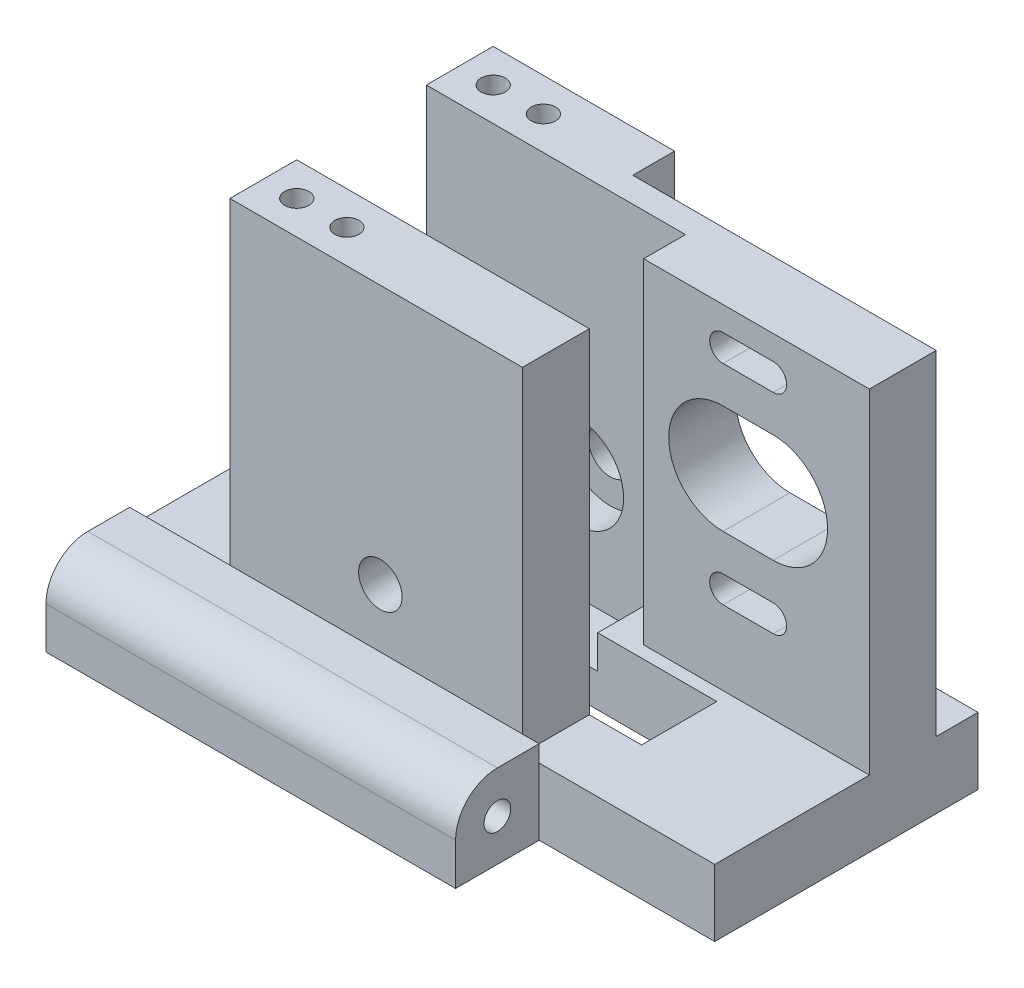
SolidWorks part; units mm, degrees
ref_plane "Front" through (0, 0, 0) normal (0, 0, 1) x (1, 0, 0)
ref_plane "Top" through (0, 0, 0) normal (0, 1, 0) x (1, 0, 0)
ref_plane "Right" through (0, 0, 0) normal (1, 0, 0) x (0, 0, -1)
sketch "Sketch1" plane through (0, 0, 0) normal (0, 1, 0) x (1, 0, 0)
  line L1 (0, 0) -> (70, 0)
  line L2 (0, 0) -> (0, -31.5)
  line L3 (0, -31.5) -> (70, -31.5)
  line L4 (70, 0) -> (70, -31.5)
  dimension "D1" = 70
  dimension "D2" = 31.5
extrude "Boss-Extrude1" add sketch "Sketch1" along normal blind 8
sketch "Sketch2" plane through (0, 8, 0) normal (0, 1, 0) x (1, 0, 0)
  line L1 (12, -31.5) -> (47, -31.5)
  line L2 (0, 0) -> (0, -31.5) construction
  line L3 (12, -23.5) -> (47, -23.5)
  line L6 (47, 0) -> (12, 0)
  line L8 (47, -8) -> (12, -8)
  line L10 (12, -8) -> (12, 0)
  line L11 (47, -8) -> (47, 0)
  line L12 (12, -23.5) -> (12, -31.5)
  line L13 (47, -23.5) -> (47, -31.5)
  dimension "D1" = 8
  dimension "D2" = 8
  dimension "D3" = 35
  dimension "D4" = 12
extrude "Boss-Extrude2" add sketch "Sketch2" along normal blind 20
sketch "Sketch3" plane through (0, 0, 31.5) normal (0, 0, 1) x (1, 0, 0)
  line L0 (0, 8) -> (0, 0) construction
  line L1 (0, 0) -> (70, 0) construction
  circle A0 centre (30, 17) radius 2.6
  dimension "D1" = 5.2
  dimension "D2" = 30
  dimension "D3" = 17
extrude "Cut-Extrude1" cut sketch "Sketch3" against normal through all
sketch "Sketch4" plane through (0, 0, 0) normal (0, 0, -1) x (-1, 0, 0)
  line L0 (-70, 0) -> (0, 0) construction
  line L1 (-49, 0) -> (0, 0)
  line L2 (-49, 0) -> (-49, 10)
  line L3 (-49, 10) -> (0, 10)
  line L4 (0, 0) -> (0, 10)
  dimension "D1" = 49
  dimension "D2" = 21
  dimension "D3" = 10
extrude "Boss-Extrude3" add sketch "Sketch4" along normal blind 10
sketch "Sketch5" plane through (0, 0, 0) normal (-1, 0, 0) x (0, 0, 1)
  line L0 (-10, 10) -> (0, 10) construction
  line L1 (-10, 0) -> (-10, 10) construction
  circle A0 centre (-5, 5) radius 1.6
  dimension "D1" = 3.2
  dimension "D2" = 5
  dimension "D3" = 5
extrude "Cut-Extrude2" cut sketch "Sketch5" against normal through all
sketch "Sketch6" plane through (0, 8, 0) normal (0, 1, 0) x (1, 0, 0)
  line L0 (47, -23.5) -> (12, -23.5) construction
  line L1 (7.25, -23.5) -> (53.25, -23.5)
  line L2 (7.25, -23.5) -> (7.25, -14.5)
  line L3 (7.25, -14.5) -> (53.25, -14.5)
  line L4 (53.25, -23.5) -> (53.25, -14.5)
  line L6 (0, 0) -> (0, -31.5) construction
  dimension "D1" = 9
  dimension "D2" = 46
  dimension "D3" = 7.25
extrude "Cut-Extrude3" cut sketch "Sketch6" against normal through all
sketch "Sketch7" plane through (0, 0, 8) normal (0, 0, 1) x (1, 0, 0)
  circle A0 centre (30, 17) radius 5.6
  dimension "D1" = 11.2
extrude "Cut-Extrude4" cut sketch "Sketch7" against normal blind 4
sketch "Sketch8" plane through (0, 0, 23.5) normal (0, 0, -1) x (-1, 0, 0)
  circle A0 centre (-30, 17) radius 5.6
  dimension "D1" = 11.2
extrude "Cut-Extrude5" cut sketch "Sketch8" against normal blind 4
sketch "Sketch9" plane through (0, 8, 0) normal (0, 1, 0) x (1, 0, 0)
  line L0 (12, -8) -> (47, -8) construction
  line L1 (21, -8) -> (39, -8)
  line L2 (21, -8) -> (21, -14.5)
  line L3 (21, -14.5) -> (39, -14.5)
  line L4 (39, -8) -> (39, -14.5)
  line L5 (53.25, -14.5) -> (7.25, -14.5) construction
  line L6 (0, 0) -> (0, -31.5) construction
  dimension "D1" = 18
  dimension "D2" = 21
extrude "Cut-Extrude6" cut sketch "Sketch9" against normal blind 4
sketch "Sketch13" plane through (0, 8, 0) normal (0, 1, 0) x (1, 0, 0)
  line L0 (70, -13) -> (43, -13)
  line L1 (70, -31.5) -> (70, 0) construction
  line L2 (43, -13) -> (43, -8)
  line L3 (39, -8) -> (47, -8) construction
  line L4 (43, -8) -> (47, -8)
  line L5 (47, -8) -> (47, -5)
  line L6 (47, -8) -> (47, 0) construction
  line L7 (47, -5) -> (70, -5)
  line L8 (70, -5) -> (70, -13)
  dimension "D1" = 5
  dimension "D2" = 3
  dimension "D3" = 27
extrude "Boss-Extrude5" add sketch "Sketch13" along normal blind 20
sketch "Sketch14" plane through (0, 0, 0) normal (0, 0, -1) x (-1, 0, 0)
  line L0 (-33.6979, 28) -> (-40.8745, 10)
  line L1 (-47, 28) -> (-12, 28) construction
  line L2 (-12, 10) -> (-47, 10) construction
  line L3 (-40.8745, 10) -> (-47, 10)
  line L4 (-47, 28) -> (-47, 10) construction
  line L5 (-47, 10) -> (-49, 10) construction
  line L6 (-47, 10) -> (-47, 28)
  line L7 (-47, 28) -> (-33.6979, 28)
extrude "Cut-Extrude10" cut sketch "Sketch14" against normal blind 5
sketch "Sketch15" plane through (0, 28, 0) normal (0, 1, 0) x (1, 0, 0)
  line L0 (70, -5) -> (70, -13)
  line L1 (70, -13) -> (70, -5) construction
  line L2 (70, -5) -> (33.6979, -5) construction
  line L3 (70, -13) -> (43, -13)
  line L4 (43, -13) -> (70, -13) construction
  line L5 (43, -13) -> (43, -8)
  line L6 (43, -8) -> (43, -13) construction
  line L7 (12, -8) -> (43, -8) construction
  line L8 (70, -5) -> (33.6979, -5)
  line L9 (12, 0) -> (24.1578, 0)
  line L10 (33.6979, -8) -> (43, -8)
  line L11 (33.6979, -8) -> (24.1578, -8)
  line L12 (12, -8) -> (24.1578, -8)
  line L13 (33.6979, 0) -> (12, 0) construction
  line L14 (24.1578, 0) -> (33.6979, 0)
  line L15 (33.6979, 0) -> (33.6979, -5)
  line L16 (12, 0) -> (12, -8)
extrude "Boss-Extrude6" add sketch "Sketch15" along normal blind 20
sketch "Sketch16" plane through (0, 0, 13) normal (0, 0, 1) x (1, 0, 0)
  line L0 (52.5, 31) -> (58.5, 31) construction
  line L1 (52.5, 37.5) -> (58.5, 37.5)
  line L3 (52.5, 24.5) -> (58.5, 24.5)
  line L4 (70, 48) -> (70, 8) construction
  line L5 (43, 48) -> (70, 48) construction
  line L6 (52.5, 43.5) -> (58.5, 43.5) construction
  line L7 (52.5, 45.1) -> (58.5, 45.1)
  line L8 (52.5, 41.9) -> (58.5, 41.9)
  line L9 (52.5, 18.5) -> (58.5, 18.5) construction
  line L10 (52.5, 20.1) -> (58.5, 20.1)
  line L11 (52.5, 16.9) -> (58.5, 16.9)
  arc A0 (52.5, 37.5) -> (52.5, 24.5) centre (52.5, 31) ccw
  arc A1 (58.5, 24.5) -> (58.5, 37.5) centre (58.5, 31) ccw
  arc A2 (52.5, 45.1) -> (52.5, 41.9) centre (52.5, 43.5) ccw
  arc A3 (58.5, 41.9) -> (58.5, 45.1) centre (58.5, 43.5) ccw
  arc A4 (52.5, 20.1) -> (52.5, 16.9) centre (52.5, 18.5) ccw
  arc A5 (58.5, 16.9) -> (58.5, 20.1) centre (58.5, 18.5) ccw
  point P2 (55.5, 31)
  point P13 (55.5, 43.5)
  point P21 (55.5, 18.5)
  dimension "D1" = 6
  dimension "D2" = 6.5
  dimension "D3" = 14.5
  dimension "D8" = 1.6
  dimension "D4" = 17
  dimension "D5" = 6
  dimension "D6" = 14.5
  dimension "D7" = 12.5
  dimension "D9" = 2
extrude "Cut-Extrude11" cut sketch "Sketch16" against normal through all
sketch "Sketch17" plane through (0, 0, 31.5) normal (0, 0, 1) x (1, 0, 0)
  line L0 (0, 0) -> (70, 0) construction
  line L1 (0, 0) -> (49, 0)
  line L2 (0, 0) -> (0, 10)
  line L3 (0, 10) -> (49, 10)
  line L4 (49, 0) -> (49, 10)
  line L5 (70, 8) -> (70, 0) construction
  dimension "D1" = 10
  dimension "D2" = 49
  dimension "D3" = 21
extrude "Boss-Extrude7" add sketch "Sketch17" along normal blind 10
sketch "Sketch18" plane through (0, 0, 0) normal (-1, 0, 0) x (0, 0, 1)
  line L0 (41.5, 10) -> (31.5, 10) construction
  line L1 (41.5, 10) -> (41.5, 0) construction
  circle A0 centre (36.5, 5) radius 1.6
  dimension "D1" = 3.2
  dimension "D2" = 5
  dimension "D3" = 5
extrude "Cut-Extrude12" cut sketch "Sketch18" against normal through all
sketch "Sketch19" plane through (0, 28, 0) normal (0, 1, 0) x (1, 0, 0)
  line L0 (12, -31.5) -> (47, -31.5) construction
  line L1 (47, -31.5) -> (12, -31.5)
  line L2 (47, -31.5) -> (47, -23.5)
  line L3 (47, -23.5) -> (12, -23.5)
  line L4 (12, -31.5) -> (12, -23.5)
  line L5 (47, -23.5) -> (12, -23.5) construction
extrude "Boss-Extrude8" add sketch "Sketch19" along normal blind 20
sketch "Sketch23" plane through (0, 48, 0) normal (0, 1, 0) x (1, 0, 0)
  line L0 (33.6979, 0) -> (12, 0) construction
  line L1 (12, -31.5) -> (47, -31.5) construction
  line L2 (12, 0) -> (12, -8) construction
  line L3 (12, -23.5) -> (12, -31.5) construction
  circle A0 centre (16, -27.5) radius 1.45
  circle A1 centre (16, -4) radius 1.45
  circle A2 centre (22, -27.5) radius 1.45
  circle A3 centre (22, -4) radius 1.45
  dimension "D1" = 2.9
  dimension "D2" = 2.9
  dimension "D3" = 4
  dimension "D4" = 4
  dimension "D5" = 4
  dimension "D6" = 4
  dimension "D7" = 2
extrude "Cut-Extrude13" cut sketch "Sketch23" against normal through all
fillet "Fillet1" radius 5 2 edges at (24.5, 10, -10) (24.5, 10, 41.5)
